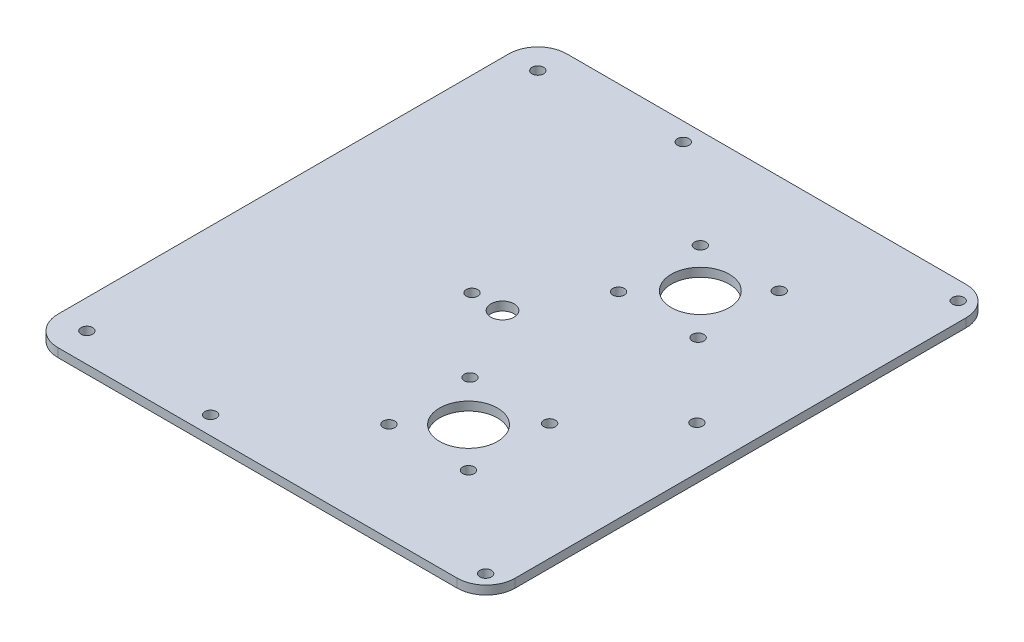
SolidWorks part; units mm, degrees
ref_plane "前视基准面" through (0, 0, 0) normal (0, 0, 1) x (1, 0, 0)
ref_plane "上视基准面" through (0, 0, 0) normal (0, 1, 0) x (1, 0, 0)
ref_plane "右视基准面" through (0, 0, 0) normal (1, 0, 0) x (0, 0, -1)
sketch "草图1" plane through (0, 0, 0) normal (0, 1, 0) x (1, 0, 0)
  line L0 (-78.915, 77.83) -> (-78.915, -77.83)
  line L1 (-1000, 0) -> (49000, 0) construction
  line L3 (-68.915, -87.83) -> (68.915, -87.83)
  line L5 (-68.915, 87.83) -> (68.915, 87.83)
  line L6 (78.915, 77.83) -> (78.915, -77.83)
  line L9 (-28.915, -912.17) -> (-28.915, 49087.83) construction
  line L10 (25, -960.3663) -> (25, 49039.6337) construction
  arc A0 (-78.915, -77.83) -> (-68.915, -87.83) centre (-68.915, -77.83) ccw
  arc A1 (68.915, -87.83) -> (78.915, -77.83) centre (68.915, -77.83) ccw
  arc A2 (78.915, 77.83) -> (68.915, 87.83) centre (68.915, 77.83) ccw
  arc A3 (-68.915, 87.83) -> (-78.915, 77.83) centre (-68.915, 77.83) ccw
  circle A4 centre (72.465, 81.57) radius 2
  circle A5 centre (72.465, -81.57) radius 2
  circle A6 centre (-22.465, -81.57) radius 2
  circle A7 centre (-22.465, 81.57) radius 2
  circle A8 centre (-68.915, 77.83) radius 2
  circle A9 centre (-68.915, -77.83) radius 2
  circle A10 centre (25, 40) radius 10
  circle A13 centre (38.6102, 53.6337) radius 2
  circle A14 centre (38.6102, 25.6337) radius 2
  circle A15 centre (11.1442, 25.6337) radius 2
  circle A18 centre (25, -40) radius 10
  circle A21 centre (11.1442, -25.6337) radius 2
  circle A22 centre (38.6102, -25.6337) radius 2
  circle A23 centre (38.6102, -53.6337) radius 2
  circle A24 centre (11.1442, -53.6337) radius 2
  circle A26 centre (11.3898, 53.6337) radius 2
  circle A27 centre (63.8263, 0) radius 2
  circle A28 centre (-13.8263, 0) radius 2
  circle A29 centre (-3.2902, 0) radius 4
  point P7 (-0.1228, -0.7844)
  point P8 (0, 0)
  point P10 (-0.1228, -0.7844)
  point P11 (0, 0)
  point P24 (25, 39.6337)
  point P25 (25, 40)
  dimension "D6" = 4
  dimension "D9" = 4
  dimension "D1" = 38.8263
  dimension "D2" = 8
  dimension "D7" = 6.26
  dimension "D8" = 6.45
extrude "凸台-拉伸1" add sketch "草图1" along normal blind 3
